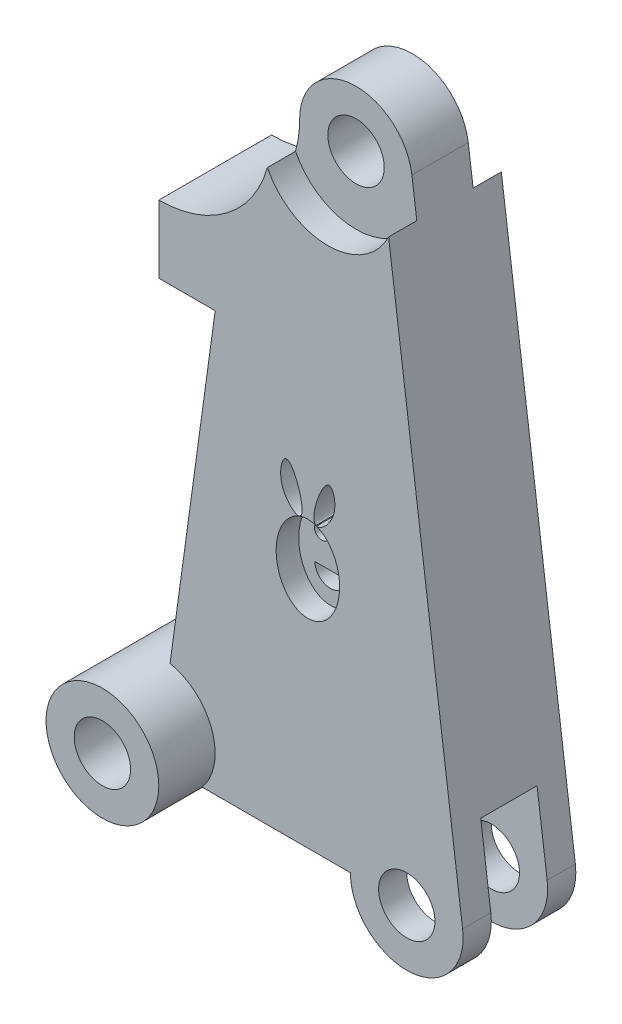
SolidWorks part; units mm, degrees
ref_plane "Front Plane" through (0, 0, 0) normal (0, 0, 1) x (1, 0, 0)
ref_plane "Top Plane" through (0, 0, 0) normal (0, 1, 0) x (1, 0, 0)
ref_plane "Right Plane" through (0, 0, 0) normal (1, 0, 0) x (0, 0, -1)
sketch "Sketch2" plane through (0, 0, 0) normal (0, 0, 1) x (1, 0, 0)
  circle A0 centre (0, 0) radius 5
  dimension "D1" = 10
extrude "Boss-Extrude1" add sketch "Sketch2" along normal mid plane 20
sketch "Sketch3" plane through (0, 0, 0) normal (0, 0, 1) x (1, 0, 0)
  line L0 (1, 4.899) -> (5, 34)
  line L1 (5, 34) -> (0, 34)
  line L2 (0, 34) -> (0, 40)
  line L3 (19.9572, 50.6525) -> (26.9572, -2.5289)
  line L4 (17, -3.1814) -> (3.8573, -3.1814)
  line L5 (3.8573, -3.1814) -> (1, 4.899)
  circle A0 centre (0, 0) radius 5 construction
  arc A1 (0, 40) -> (10, 50) centre (0, 50) ccw
  arc A3 (26.9572, -2.5289) -> (17, -3.1814) centre (22, -3.1814) cw
  arc A4 (10, 50) -> (19.9572, 50.6525) centre (15, 50) cw
  dimension "D1" = 5
  dimension "D2" = 5
  dimension "D4" = 10
  dimension "D3" = 22
  dimension "D5" = 6
  dimension "D6" = 50
  dimension "D7" = 1
  dimension "D8" = 5
  dimension "D9" = 53.1814
  dimension "D10" = 29.101
  dimension "D11" = 17.0025
extrude "Boss-Extrude2" add sketch "Sketch3" along normal mid plane 10
sketch "Sketch4" plane through (0, 0, 5) normal (0, 0, 1) x (1, 0, 0)
  circle A0 centre (15, 50) radius 2.5
  circle A1 centre (0, 0) radius 2.5
  circle A2 centre (22, -3.1814) radius 2.5
  dimension "D1" = 5
extrude "Cut-Extrude1" cut sketch "Sketch4" against normal through all and the other way through all
sketch "Sketch5" plane through (0, 0, 5) normal (0, 0, 1) x (1, 0, 0)
  circle A0 centre (15, 50) radius 6
  dimension "D1" = 12
extrude "Cut-Extrude2" cut sketch "Sketch5" against normal blind 2.5
mirror "Mirror1" about plane through (0, 0, 0) normal (0, 0, 1) of "Cut-Extrude2"
sketch "Sketch7" plane through (0, 0, 0) normal (0, 0, 1) x (1, 0, 0)
  circle A0 centre (22, -3.1814) radius 8.5
  dimension "D1" = 17
extrude "Cut-Extrude3" cut sketch "Sketch7" against normal blind 2.5 and the other way blind 2.5
sketch "Sketch9" plane through (0, 0, 5) normal (0, 0, 1) x (1, 0, 0)
  ellipse E0 centre (13.2279, 18.2819) end of major axis (13.2279, 22.0899) minor radius 2.8132
extrude "Cut-Extrude4" cut sketch "Sketch9" against normal blind 2
sketch "Sketch11" plane through (0, 0, 5) normal (0, 0, 1) x (1, 0, 0)
  ellipse E0 centre (13.2279, 18.2819) end of major axis (13.2279, 22.0899) minor radius 2.8132 construction
  ellipse E2 centre (13.2279, 18.2819) end of major axis (13.2279, 22.0899) minor radius 2.8132 construction
  spline S0 degree 3 poles (11.3692, 27.9077) (13.784, 20.4246) (10.3594, 23.3179) (11.3692, 27.9077) (13.784, 20.4246) (10.3594, 23.3179) knots -1 -0.748321 -0.470665 0 0.251679 0.529335 1 1.251679 1.529335 2 only from (12.522, 21.9681) to (12.522, 21.9681)
  spline S1 degree 3 poles (15.0693, 27.6277) (12.6954, 20.4194) (16.0567, 23.2944) (15.0693, 27.6277) (12.6954, 20.4194) (16.0567, 23.2944) knots -1 -0.736578 -0.470499 0 0.263422 0.529501 1 1.263422 1.529501 2 only from (13.9337, 21.9681) to (13.9337, 21.9681)
  point P13 (13.2279, 22.0899)
  dimension "D1" = 2.2489
  dimension "D2" = 2.25
  dimension "D3" = 1.9088
  dimension "D4" = 1.91
extrude "Cut-Extrude5" cut sketch "Sketch11" against normal blind 2
sketch "Sketch12" plane through (0, 0, 3) normal (0, 0, 1) x (1, 0, 0)
  circle A0 centre (12.4661, 19.7457) radius 0.65
  circle A1 centre (13.9337, 19.7457) radius 0.65
  dimension "D1" = 1.3
extrude "Cut-Extrude6" cut sketch "Sketch12" against normal through all
sketch "Sketch13" plane through (0, 0, 3) normal (0, 0, 1) x (1, 0, 0)
  line L0 (11.8481, 17.1569) -> (14.6076, 17.1569)
  arc A3 (11.8481, 17.1569) -> (14.6076, 17.1569) centre (13.2279, 17.1569) ccw
extrude "Cut-Extrude7" cut sketch "Sketch13" against normal through all
mirror "Mirror2" about plane through (0, 0, 0) normal (0, 0, 1) of "Cut-Extrude4", "Cut-Extrude5"
